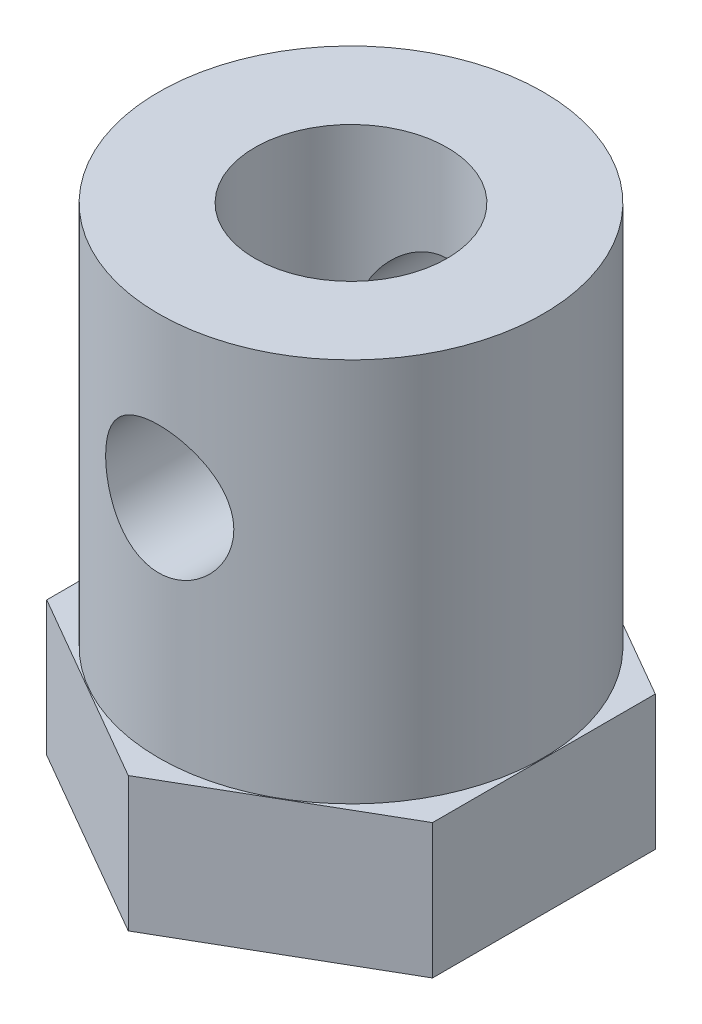
SolidWorks part; units mm, degrees
ref_plane "Alzado" through (0, 0, 0) normal (0, 0, 1) x (1, 0, 0)
ref_plane "Planta" through (0, 0, 0) normal (0, 1, 0) x (1, 0, 0)
ref_plane "Vista lateral" through (0, 0, 0) normal (1, 0, 0) x (0, 0, -1)
sketch "Croquis1" plane through (0, 0, 0) normal (0, 1, 0) x (1, 0, 0)
  line L1 (0, 6.9513) -> (-6.02, 3.4756)
  line L2 (-6.02, 3.4756) -> (-6.02, -3.4756)
  line L3 (-6.02, -3.4756) -> (0, -6.9513)
  line L4 (0, -6.9513) -> (6.02, -3.4756)
  line L5 (6.02, -3.4756) -> (6.02, 3.4756)
  line L6 (6.02, 3.4756) -> (0, 6.9513)
  circle A0 centre (0, 0) radius 6.02 construction
  dimension "D1" = 12.04
extrude "Saliente-Extruir1" add sketch "Croquis1" along normal blind 4.2
sketch "Croquis2" plane through (0, 4.2, 0) normal (0, 1, 0) x (1, 0, 0)
  circle A0 centre (0, 0) radius 6
  dimension "D1" = 12
extrude "Saliente-Extruir2" add sketch "Croquis2" along normal blind 12
sketch "Croquis3" plane through (0, 16.2, 0) normal (0, 1, 0) x (1, 0, 0)
  circle A0 centre (0, 0) radius 3
  dimension "D1" = 6
extrude "Cortar-Extruir1" cut sketch "Croquis3" against normal through all
sketch "Croquis4" plane through (0, 0, 0) normal (0, 0, 1) x (1, 0, 0)
  line L0 (6, 16.2) -> (-6, 16.2) construction
  circle A0 centre (0, 11.2) radius 2
  dimension "D2" = 4
  dimension "D1" = 5
extrude "Cortar-Extruir2" cut sketch "Croquis4" against normal through all both and the other way through all
